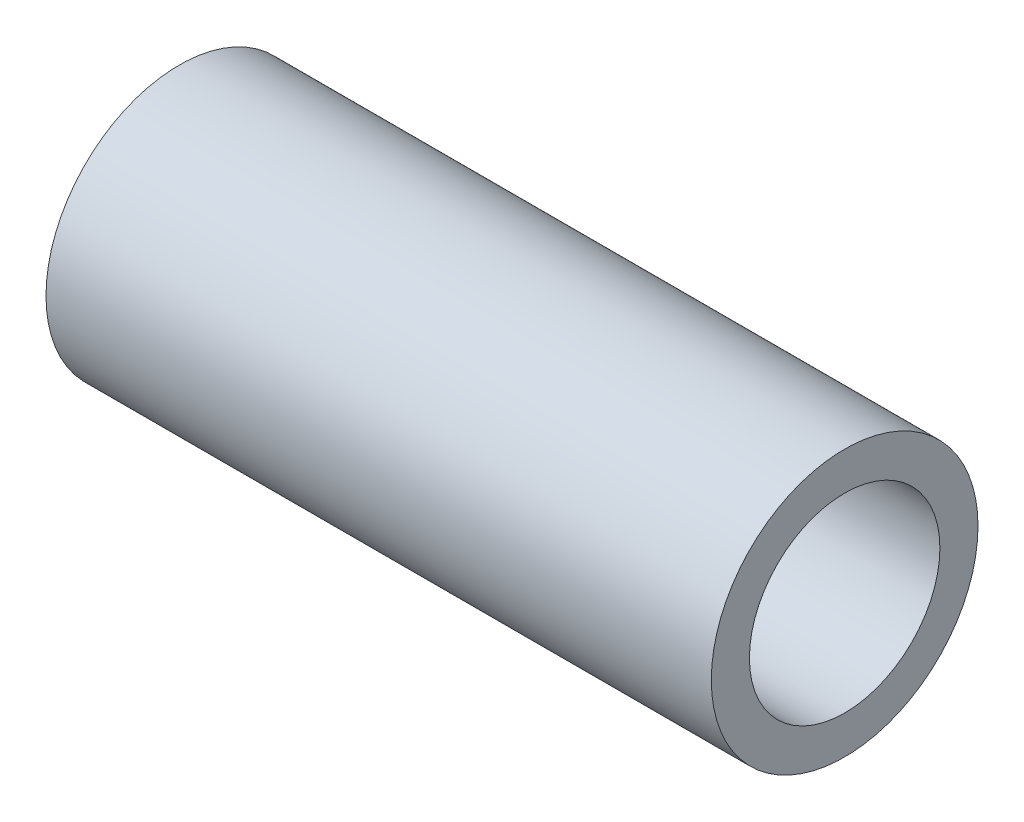
SolidWorks part; units mm, degrees
ref_plane "Front Plane" through (0, 0, 0) normal (0, 0, 1) x (1, 0, 0)
ref_plane "Top Plane" through (0, 0, 0) normal (0, 1, 0) x (1, 0, 0)
ref_plane "Right Plane" through (0, 0, 0) normal (1, 0, 0) x (0, 0, -1)
sketch "Sketch1" plane through (0, 0, 0) normal (1, 0, 0) x (0, 0, -1)
  circle A0 centre (0, 0) radius 2.5
  circle A1 centre (0, 0) radius 3.5
  dimension "D1" = 5
  dimension "D2" = 7
extrude "Boss-Extrude1" add sketch "Sketch1" along normal blind 17.4625
